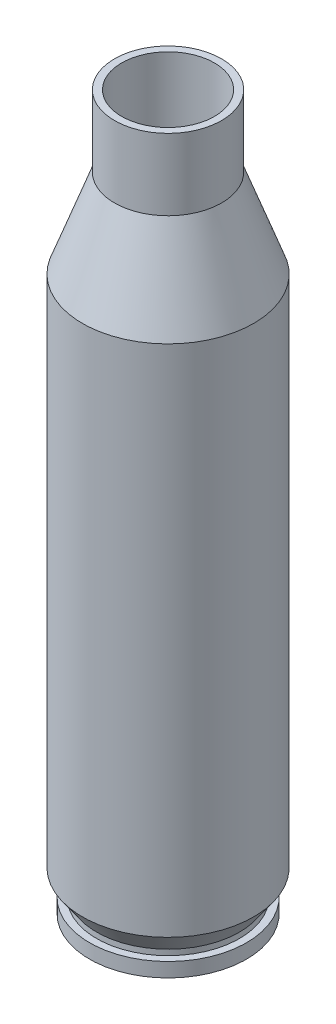
SolidWorks part; units mm, degrees
ref_plane "Plan de face" through (0, 0, 0) normal (0, 0, 1) x (1, 0, 0)
ref_plane "Plan de dessus" through (0, 0, 0) normal (0, 1, 0) x (1, 0, 0)
ref_plane "Plan de droite" through (0, 0, 0) normal (1, 0, 0) x (0, 0, -1)
sketch "Esquisse1" plane through (0, 0, 0) normal (0, 0, 1) x (1, 0, 0)
  line L0 (-3.25, 50) -> (-3.75, 50)
  line L1 (-3.75, 50) -> (-3.75, 45)
  line L2 (-3.75, 45) -> (-6, 38.8182)
  line L3 (-6, 38.8182) -> (-6, 2.8182)
  line L4 (-3.25, 50) -> (-3.25, 44.9118)
  line L5 (-3.25, 44.9118) -> (-5.3896, 39.0333)
  line L6 (-5.3896, 39.0333) -> (-5.3896, 2.8182)
  line L7 (-4.3896, 1) -> (0, 1)
  line L8 (0, 1) -> (0, 0)
  line L9 (0, 0) -> (-5.5, 0)
  line L10 (-5.5, 0) -> (-5.5, 1)
  line L11 (-5.5, 1) -> (-5, 1)
  line L12 (-5, 1) -> (-5, 1.39)
  line L13 (-5, 1.39) -> (-6, 2.8182)
  line L14 (0, 0) -> (0, 73.5844) construction
  line L15 (-4.3896, 1) -> (-4.3896, 1.39)
  line L16 (-4.3896, 1.39) -> (-5.3896, 2.8182)
  dimension "D1" = 3.25
  dimension "D2" = 50
  dimension "D3" = 0.5
  dimension "D4" = 5
  dimension "D5" = 20
  dimension "D6" = 6
  dimension "D7" = 1
  dimension "D8" = 35
  dimension "D9" = 36
  dimension "D10" = 0.5
  dimension "D11" = 0.5
  dimension "D12" = 0.5
  dimension "D13" = 0.5
revolve "Révolution1" add sketch "Esquisse1" angle 360 about L14
